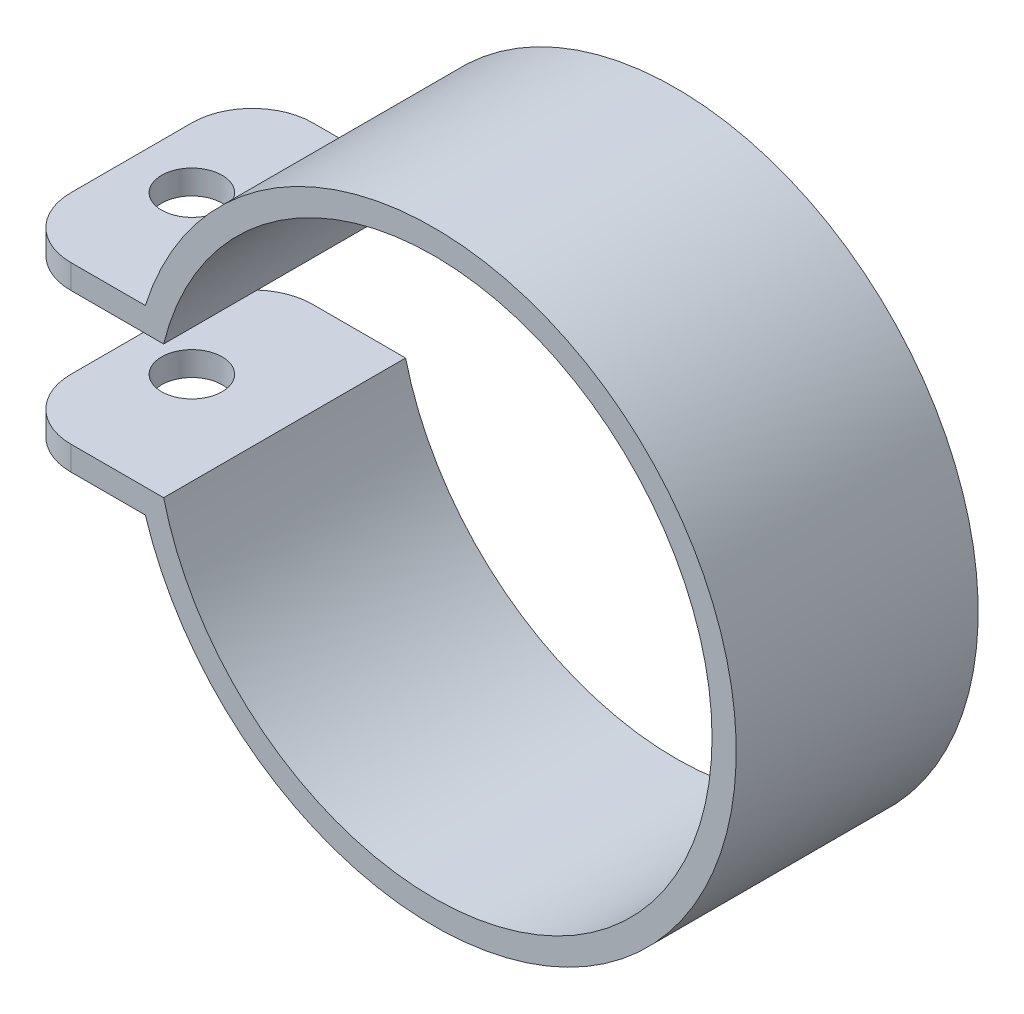
SolidWorks part; units mm, degrees
ref_plane "Front Plane" through (0, 0, 0) normal (0, 0, 1) x (1, 0, 0)
ref_plane "Top Plane" through (0, 0, 0) normal (0, 1, 0) x (1, 0, 0)
ref_plane "Right Plane" through (0, 0, 0) normal (1, 0, 0) x (0, 0, -1)
sketch "Sketch1" plane through (0, 0, 0) normal (0, 0, 1) x (1, 0, 0)
  line L0 (0, 73.5219) -> (0, -73.5219) construction
  line L1 (-96.7858, 0) -> (96.7858, 0) construction
  line L2 (-70, 15) -> (-47.697, 15)
  line L3 (-70, -15) -> (-47.697, -15)
  line L4 (-70, -11) -> (-44.6654, -11)
  line L5 (-70, 11) -> (-44.6654, 11)
  line L6 (-70, 15) -> (-70, 11)
  line L7 (-70, -11) -> (-70, -15)
  arc A0 (-47.697, -15) -> (-47.697, 15) centre (0, 0) ccw
  arc A1 (-44.6654, -11) -> (-44.6654, 11) centre (0, 0) ccw
  dimension "D1" = 100
  dimension "D2" = 30
  dimension "D3" = 70
  dimension "D4" = 4
extrude "Boss-Extrude1" add sketch "Sketch1" along normal mid plane 40
fillet "Fillet1" radius 10 4 edges at (-70, -13, -20) (-70, -13, 20) (-70, 13, -20) (-70, 13, 20)
sketch "Sketch2" plane through (0, 15, 0) normal (0, 1, 0) x (1, 0, 0)
  circle A0 centre (-60, 0) radius 5
  point P2 (0, 0)
  dimension "D1" = 10
  dimension "D2" = 60
extrude "Cut-Extrude1" cut sketch "Sketch2" against normal blind 40
